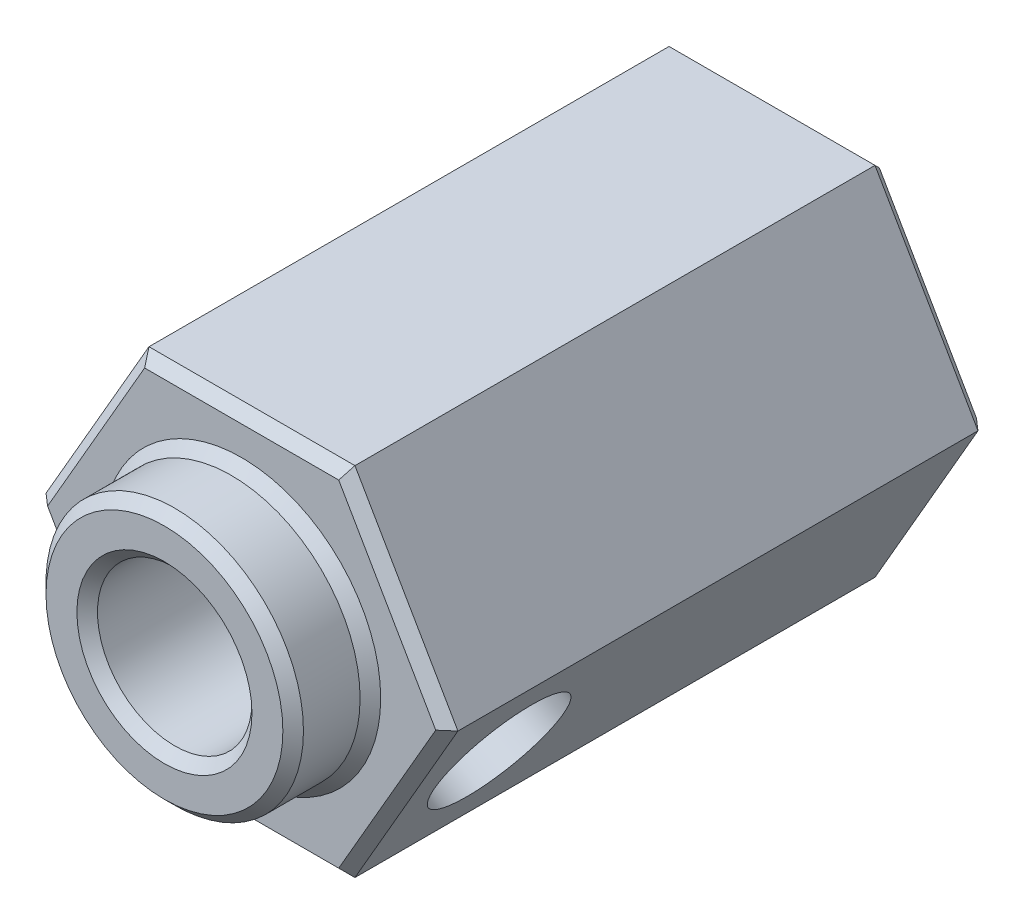
SolidWorks part; units mm, degrees
ref_plane "前视基准面" through (0, 0, 0) normal (0, 0, 1) x (1, 0, 0)
ref_plane "上视基准面" through (0, 0, 0) normal (0, 1, 0) x (1, 0, 0)
ref_plane "右视基准面" through (0, 0, 0) normal (1, 0, 0) x (0, 0, -1)
sketch "草图1" plane through (0, 0, 0) normal (0, 0, 1) x (1, 0, 0)
  line L1 (-4, 0) -> (-2, -3.4641)
  line L2 (-2, -3.4641) -> (2, -3.4641)
  line L3 (2, -3.4641) -> (4, 0)
  line L4 (4, 0) -> (2, 3.4641)
  line L5 (2, 3.4641) -> (-2, 3.4641)
  line L6 (-2, 3.4641) -> (-4, 0)
  circle A0 centre (0, 0) radius 4 construction
  dimension "D1" = 8
extrude "凸台-拉伸1" add sketch "草图1" along normal blind 12
sketch "草图2" plane through (0, 0, 12) normal (0, 0, 1) x (1, 0, 0)
  circle A0 centre (0, 0) radius 2.5
  dimension "D1" = 5
extrude "切除-拉伸1" cut sketch "草图2" against normal blind 1.5 flip side to cut
sketch "草图3" plane through (0, 0, 12) normal (0, 0, 1) x (1, 0, 0)
  circle A0 centre (0, 0) radius 1.5
  dimension "D1" = 3
extrude "切除-拉伸2" cut sketch "草图3" against normal blind 8
hole_wizard "M3 螺纹孔1" positions "草图5" profile "草图4" tap size "M3" standard "GB" end condition through all
sketch "草图5" plane through (0, 0, 4) normal (0, 0, 1) x (1, 0, 0)
  point P0 (0, 0)
sketch "草图4" plane through (0, 0, 4) normal (1, 0, 0) x (0, -1, 0)
  line L0 (0, 0) -> (0, 4)
  line L1 (0, 4) -> (1.25, 4)
  line L2 (1.25, 4) -> (1.25, 0)
  line L5 (1.25, 0) -> (0, 0)
  line L11 (0, -6.35) -> (0, 107.95) construction
  dimension "通孔螺纹孔钻头直径" = 2.5
  dimension "通孔螺纹孔钻头深度" = 4
cosmetic thread "孔螺蚊线1" parameters "D2"=3
sketch "草图6" plane through (3, -1.7321, 0) normal (0.866, -0.5, 0) x (0, 0, -1)
  line L0 (-10.5, 0) -> (0.5908, 0) construction
  line L1 (-10.5, -2) -> (-10.5, 2) construction
hole_wizard "M3 螺纹孔2" positions "3D草图1" profile "草图9" tap size "M3" standard "GB"
sketch3d "3D草图1"
  line L0 (3, -1.7321, 10.5) -> (3, -1.7321, -0.5908) construction
  line L1 (2, -3.4641, 10.5) -> (4, 0, 10.5) construction
  point P0 (3, -1.7321, 8.5)
  dimension "D1" = 2
sketch "草图9" plane through (3, -1.7321, 8.5) normal (0, 0, 1) x (0.5, 0.866, 0)
  line L0 (0, 0) -> (0, 4.2511)
  line L1 (0, 4.2511) -> (1.25, 3.5)
  line L2 (1.25, 3.5) -> (1.25, 0)
  line L5 (1.25, 0) -> (0, 0)
  line L10 (0, 4.2511) -> (-1.25, 3.5) construction
  line L11 (0, -6.35) -> (0, 107.95) construction
  dimension "螺纹孔钻头直径" = 2.5
  dimension "螺纹孔钻头深度" = 3.5
  dimension "导头角度" = 118
cosmetic thread "孔螺蚊线2" parameters "D1"=2.6349, "D2"=3
chamfer "倒角1" distance 0.2 angle 45 16 edges at (-3, -1.7321, 0) (0, -3.4641, 0) (3, -1.7321, 0) (3, 1.7321, 0) (0, 3.4641, 0) (-3, 1.7321, 0) (1.25, 0, 0) (0, 3.4641, 10.5) (3, 1.7321, 10.5) (3, -1.7321, 10.5) (0, -3.4641, 10.5) (-3, -1.7321, 10.5) (-3, 1.7321, 10.5) (2.5, 0, 10.5) (1.5, 0, 12) (2.5, 0, 12)
